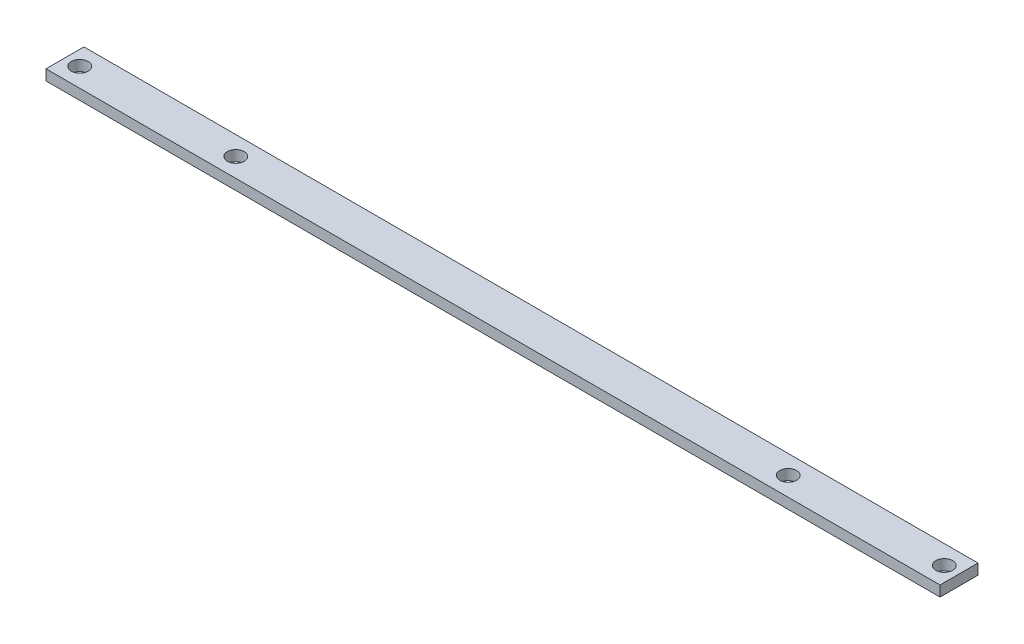
SolidWorks part; units mm, degrees
ref_plane "Front Plane" through (0, 0, 0) normal (0, 0, 1) x (1, 0, 0)
ref_plane "Top Plane" through (0, 0, 0) normal (0, 1, 0) x (1, 0, 0)
ref_plane "Right Plane" through (0, 0, 0) normal (1, 0, 0) x (0, 0, -1)
sketch "Sketch1" plane through (0, 0, 0) normal (0, 1, 0) x (1, 0, 0)
  line L0 (0, 4.5) -> (3.5, 4.5) construction
  line L1 (0, 0) -> (212, 0)
  line L2 (0, 0) -> (0, 9)
  line L3 (0, 9) -> (212, 9)
  line L4 (212, 0) -> (212, 9)
  line L5 (3.5, 4.5) -> (40.5, 4.5) construction
  line L6 (40.5, 4.5) -> (171.5, 4.5) construction
  line L7 (171.5, 4.5) -> (208.5, 4.5) construction
  line L8 (208.5, 4.5) -> (212, 4.5) construction
  circle A0 centre (3.5, 4.5) radius 2
  circle A1 centre (40.5, 4.5) radius 2
  circle A2 centre (171.5, 4.5) radius 2
  circle A3 centre (208.5, 4.5) radius 2
  dimension "D2" = 4
  dimension "D1" = 9
  dimension "D3" = 3.5
  dimension "D4" = 37
  dimension "D5" = 3.5
  dimension "D6" = 37
  dimension "D7" = 131
extrude "Boss-Extrude1" add sketch "Sketch1" along normal blind 2.5 contours L3 L4 L1 L2 | A0 | A1 | A2 | A3
